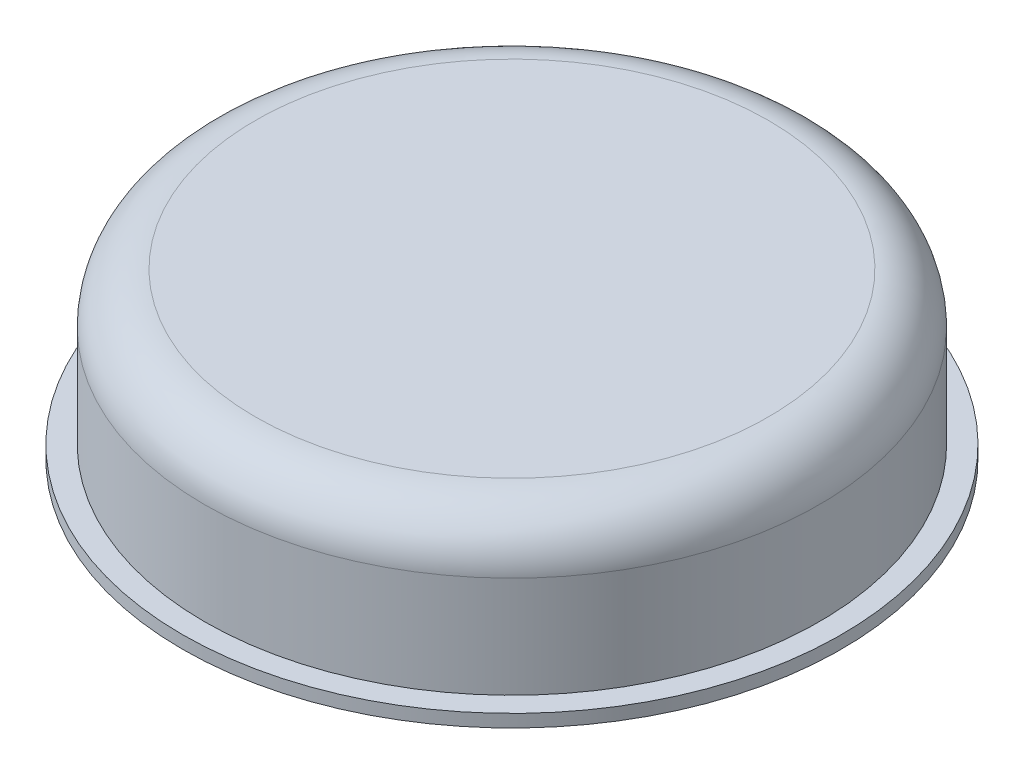
SolidWorks part; units mm, degrees
ref_plane "Front Plane" through (0, 0, 0) normal (0, 0, 1) x (1, 0, 0)
ref_plane "Top Plane" through (0, 0, 0) normal (0, 1, 0) x (1, 0, 0)
ref_plane "Right Plane" through (0, 0, 0) normal (1, 0, 0) x (0, 0, -1)
sketch "Sketch1" plane through (0, 0, 0) normal (0, 1, 0) x (1, 0, 0)
  circle A0 centre (0, 0) radius 26
  dimension "D1" = 52
extrude "Boss-Extrude1" add sketch "Sketch1" along normal blind 1
sketch "Sketch2" plane through (0, 1, 0) normal (0, 1, 0) x (1, 0, 0)
  circle A0 centre (0, 0) radius 24.25
  dimension "D1" = 48.5
extrude "Boss-Extrude2" add sketch "Sketch2" along normal blind 12
fillet "Fillet1" radius 4 1 edges at (0, 13, 24.25)
